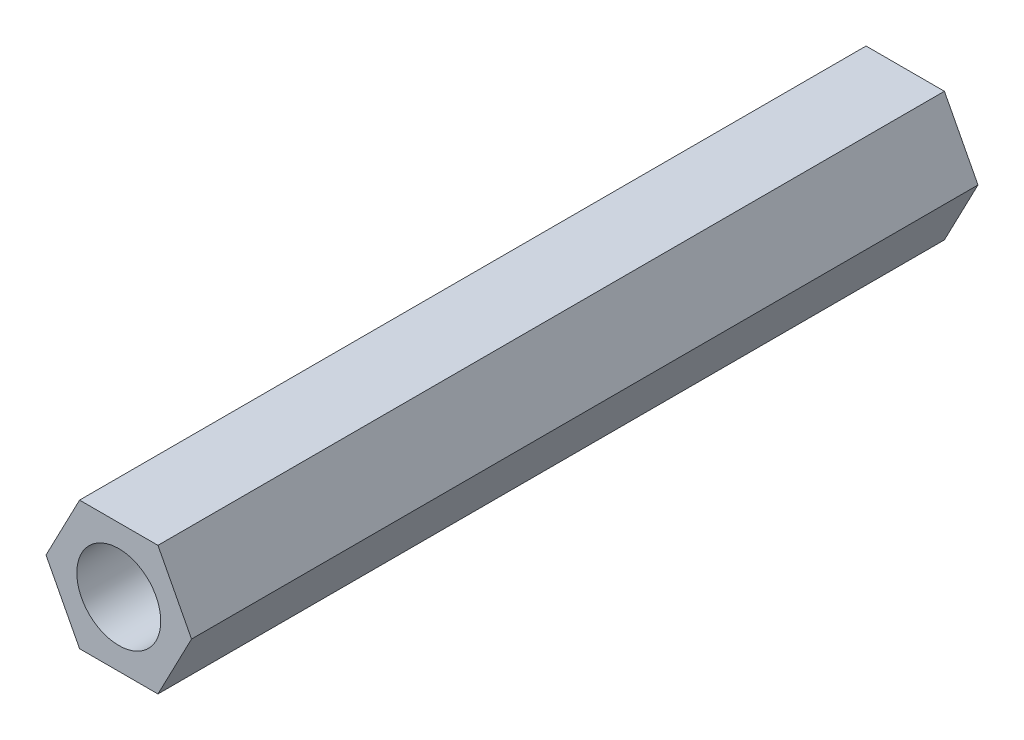
SolidWorks part; units mm, degrees
material "Bronce de aluminio"
ref_plane "Alzado" through (0, 0, 0) normal (0, 0, 1) x (1, 0, 0)
ref_plane "Planta" through (0, 0, 0) normal (0, 1, 0) x (1, 0, 0)
ref_plane "Vista lateral" through (0, 0, 0) normal (1, 0, 0) x (0, 0, -1)
sketch "Sketch1" plane through (0, 0, 0) normal (0, 0, 1) x (1, 0, 0)
  line L0 (-1.4, 4.6) -> (1.4, 4.6)
  line L1 (-1.4, 0) -> (1.4, 0)
  line L2 (-2.6, 2.3) -> (6.18, 2.3) construction
  line L3 (-1.4, 0) -> (-2.5998, 2.3)
  line L4 (-2.5998, 2.3) -> (-1.4, 4.6)
  line L5 (1.4, 0) -> (2.5998, 2.3)
  line L6 (2.5998, 2.3) -> (1.4, 4.6)
  line L7 (0, 0) -> (0, 4.6041) construction
  dimension "D1" = 4.6
  dimension "D2" = 2.8
  dimension "D3" = 2.8
  dimension "D4" = 2.3
  dimension "D5" = 2.6
extrude "Boss-Extrude1" add sketch "Sketch1" along normal blind 28.1
sketch "Sketch2" plane through (0, 0, 0) normal (0, 0, -1) x (-1, 0, 0)
  line L0 (2.5998, 2.3) -> (-2.5998, 2.3) construction
  circle A0 centre (0, 2.3) radius 1.5
  dimension "D1" = 3
extrude "Cut-Extrude1" cut sketch "Sketch2" against normal blind 2
sketch "Sketch3" plane through (0, 0, 28.1) normal (0, 0, 1) x (1, 0, 0)
  line L0 (-2.5998, 2.3) -> (2.5998, 2.3) construction
  circle A0 centre (0, 2.3) radius 1.5
  dimension "D1" = 3
extrude "Cut-Extrude2" cut sketch "Sketch3" against normal blind 3
